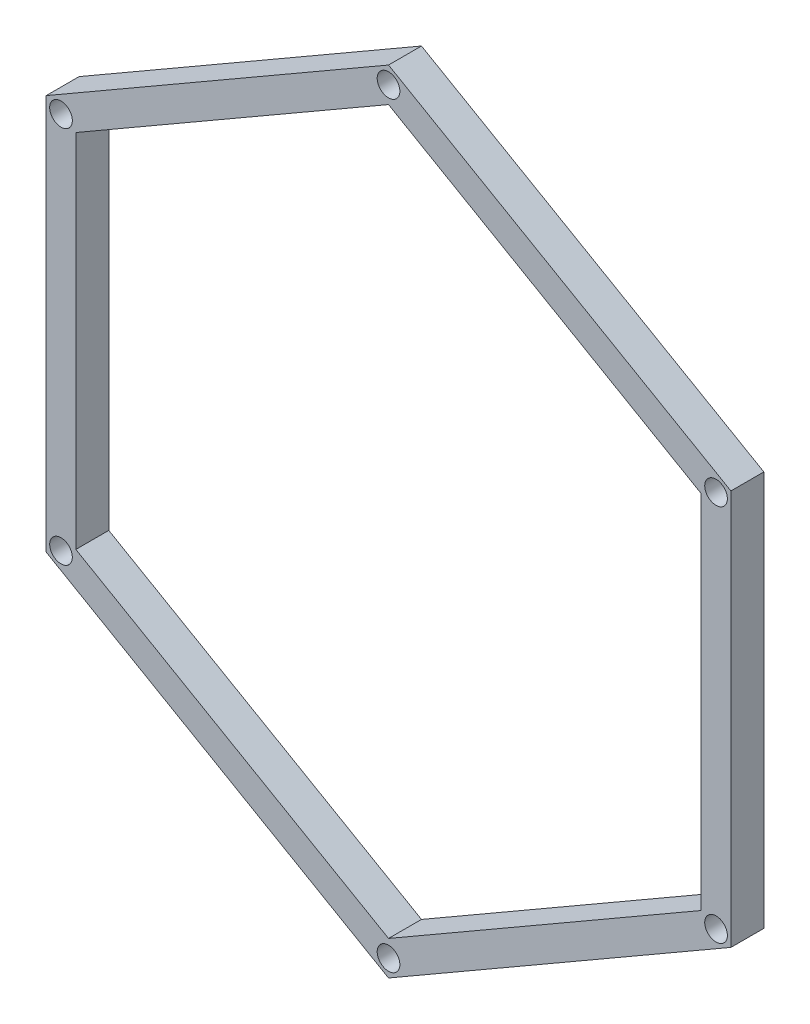
SolidWorks part; units mm, degrees
ref_plane "Front Plane" through (0, 0, 0) normal (0, 0, 1) x (1, 0, 0)
ref_plane "Top Plane" through (0, 0, 0) normal (0, 1, 0) x (1, 0, 0)
ref_plane "Right Plane" through (0, 0, 0) normal (1, 0, 0) x (0, 0, -1)
sketch "Sketch1" plane through (0, 0, 0) normal (0, 0, 1) x (1, 0, 0)
  line L0 (-32.9956, 19.05) -> (-30.136, 17.399) construction
  line L1 (32.9956, 19.05) -> (0, 38.1)
  line L2 (0, 38.1) -> (-32.9956, 19.05)
  line L3 (-32.9956, 19.05) -> (-32.9956, -19.05)
  line L4 (-32.9956, -19.05) -> (0, -38.1)
  line L5 (0, -38.1) -> (32.9956, -19.05)
  line L6 (32.9956, -19.05) -> (32.9956, 19.05)
  line L7 (30.136, 17.399) -> (0, 34.798)
  line L8 (0, 34.798) -> (-30.136, 17.399)
  line L9 (-30.136, 17.399) -> (-30.136, -17.399)
  line L10 (-30.136, -17.399) -> (0, -34.798)
  line L11 (0, -34.798) -> (30.136, -17.399)
  line L12 (30.136, -17.399) -> (30.136, 17.399)
  circle A0 centre (0, 0) radius 32.9956 construction
  circle A1 centre (0, 0) radius 30.136 construction
  circle A2 centre (-31.5658, 18.2245) radius 1.0922
  circle A3 centre (0, 36.449) radius 1.0922
  circle A4 centre (0, 0) radius 30.136 construction
  circle A5 centre (31.5658, 18.2245) radius 1.0922
  circle A6 centre (0, 0) radius 30.136 construction
  circle A7 centre (31.5658, -18.2245) radius 1.0922
  circle A8 centre (0, 0) radius 30.136 construction
  circle A9 centre (0, -36.449) radius 1.0922
  circle A10 centre (0, 0) radius 30.136 construction
  circle A11 centre (-31.5658, -18.2245) radius 1.0922
  circle A12 centre (0, 0) radius 30.136 construction
  point P36 (0, 0)
  dimension "D3" = 2.1844
  dimension "D4" = 6
  dimension "D1" = 38.1
  dimension "D2" = 34.798
extrude "Boss-Extrude1" add sketch "Sketch1" along normal blind 3.175
